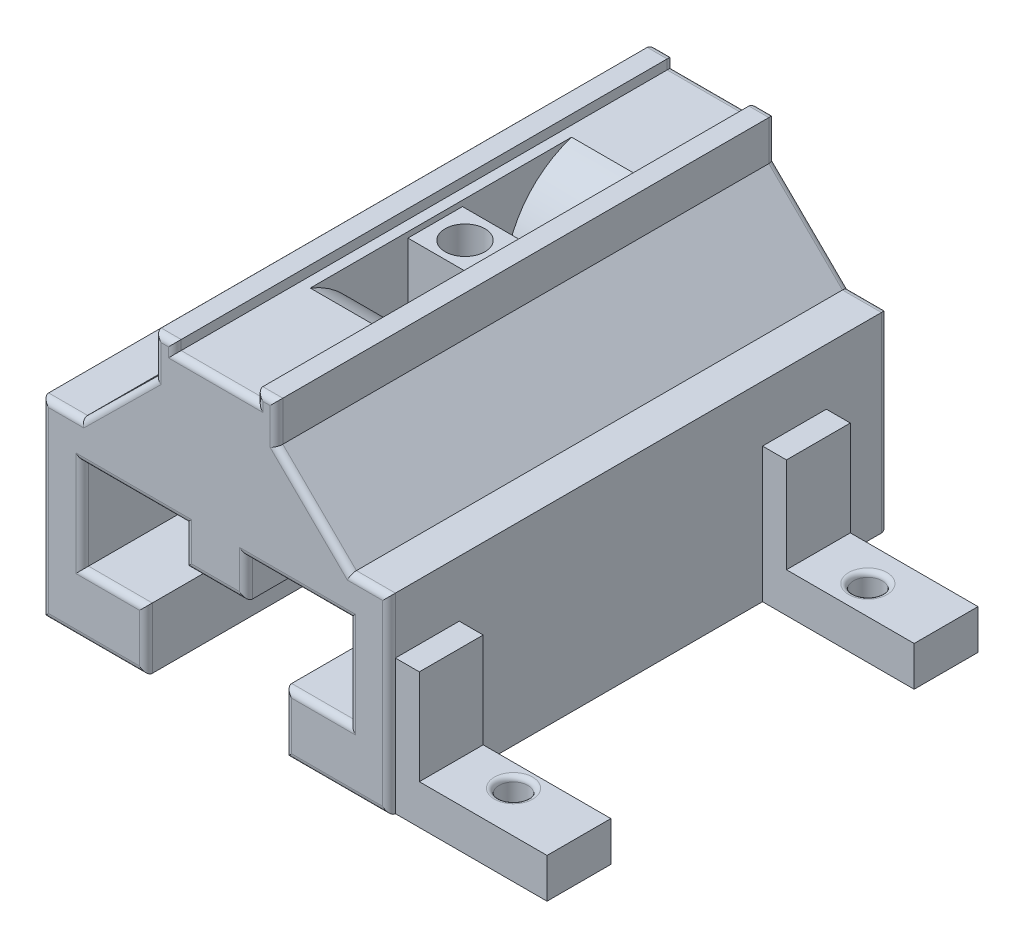
SolidWorks part; units mm, degrees
ref_plane "Front" through (0, 0, 0) normal (0, 0, 1) x (1, 0, 0)
ref_plane "Top" through (0, 0, 0) normal (0, 1, 0) x (1, 0, 0)
ref_plane "Right" through (0, 0, 0) normal (1, 0, 0) x (0, 0, -1)
sketch "Sketch2" plane through (0, 0, 0) normal (0, 0, 1) x (1, 0, 0)
  line L0 (-5.545, 3.0291) -> (-10.62, 3.0291)
  line L1 (-10.62, 3.0291) -> (-10.62, 10.3311)
  line L2 (-10.62, 10.3311) -> (-2.42, 10.3311)
  line L3 (-2.42, 10.3311) -> (-2.42, 7.2831)
  line L4 (-2.42, 7.2831) -> (2.42, 7.2831)
  line L5 (0, -13.7255) -> (0, 13.7255) construction
  line L6 (-5.545, 3.0291) -> (-5.545, -1.8209)
  line L7 (-5.545, -1.8209) -> (-13.795, -1.8209)
  line L8 (-13.795, -1.8209) -> (-13.795, 13.3791)
  line L9 (-13.795, 13.3791) -> (-10.695, 13.3791)
  line L10 (-10.695, 13.3791) -> (-4.8375, 19.1576)
  line L11 (-4.8375, 19.1576) -> (-4.8375, 22.3326)
  line L12 (-4.8375, 22.3326) -> (-3.25, 22.3326)
  line L13 (-3.25, 22.3326) -> (-3.25, 21.5706)
  line L14 (-3.25, 21.5706) -> (3.25, 21.5706)
  line L15 (3.25, 22.3326) -> (3.25, 21.5706)
  line L16 (4.8375, 22.3326) -> (3.25, 22.3326)
  line L17 (4.8375, 19.1576) -> (4.8375, 22.3326)
  line L18 (10.695, 13.3791) -> (4.8375, 19.1576)
  line L19 (13.795, 13.3791) -> (10.695, 13.3791)
  line L20 (13.795, -1.8209) -> (13.795, 13.3791)
  line L21 (5.545, -1.8209) -> (13.795, -1.8209)
  line L22 (5.545, 3.0291) -> (5.545, -1.8209)
  line L23 (2.42, 10.3311) -> (2.42, 7.2831)
  line L24 (10.62, 10.3311) -> (2.42, 10.3311)
  line L25 (10.62, 3.0291) -> (10.62, 10.3311)
  line L26 (5.545, 3.0291) -> (10.62, 3.0291)
  point P23 (0, 21.5706)
  point P32 (0, 7.2831)
  dimension "D1" = 4.85
  dimension "D2" = 8.25
  dimension "D3" = 3.175
  dimension "D4" = 15.2
  dimension "D5" = 3.048
  dimension "D6" = 3.048
  dimension "D7" = 14.2875
  dimension "D8" = 3.175
  dimension "D9" = 0.762
  dimension "D10" = 1.5875
  dimension "D11" = 3.25
  dimension "D12" = 3.1
  dimension "D13" = 8.2
  dimension "D14" = 2.42
extrude "Boss-Extrude1" add sketch "Sketch2" along normal blind 39.6875
sketch "Sketch3" plane through (0, 21.5706, 0) normal (0, 1, 0) x (1, 0, 0)
  line L0 (0, 0) -> (0, -39.6875) construction
  line L1 (-13.795, -19.8438) -> (13.795, -19.8438) construction
  line L2 (-13.795, -39.6875) -> (-13.795, 0) construction
  line L3 (13.795, -39.6875) -> (13.795, 0) construction
  line L4 (3.25, 0) -> (-3.25, 0)
  line L5 (-3.25, 0) -> (-3.25, -39.6875)
  line L6 (-3.25, -39.6875) -> (3.25, -39.6875)
  line L7 (3.25, -39.6875) -> (3.25, 0)
  line L8 (3.25, 0) -> (-3.25, 0)
  line L9 (-3.25, 0) -> (-3.25, -39.6875)
  line L10 (-3.25, -39.6875) -> (3.25, -39.6875)
  line L11 (3.25, -39.6875) -> (3.25, 0)
  circle A0 centre (0, -19.8437) radius 1.5875
  dimension "D2" = 3.175
  dimension "D1" = 0
extrude "Cut-Extrude1" cut sketch "Sketch3" against normal blind 39.6875 contours A0
sketch "Sketch4" plane through (0, 7.2831, 0) normal (0, -1, 0) x (1, 0, 0)
  line L1 (2.0785, 16.2437) -> (4.1569, 19.8437)
  line L2 (4.1569, 19.8437) -> (2.0785, 23.4437)
  line L3 (2.0785, 23.4437) -> (-2.0785, 23.4437)
  line L4 (-2.42, 0) -> (2.42, 0)
  line L5 (2.42, 0) -> (2.42, 39.6875)
  line L6 (2.42, 39.6875) -> (-2.42, 39.6875)
  line L8 (-2.42, 0) -> (2.42, 0)
  line L9 (2.42, 0) -> (2.42, 39.6875)
  line L12 (-2.0785, 23.4437) -> (-4.1569, 19.8437)
  line L13 (-4.1569, 19.8437) -> (-2.0785, 16.2437)
  line L14 (-2.0785, 16.2437) -> (2.0785, 16.2437)
  line L18 (2.42, 39.6875) -> (-2.42, 39.6875)
  line L20 (-2.42, 39.6875) -> (-2.42, 0)
  line L21 (-2.42, 39.6875) -> (-2.42, 0)
  circle A0 centre (0, 19.8437) radius 3.6 construction
  circle M11 centre (0, 19.8437) radius 1.5875
  dimension "D2" = 7.2
  dimension "D1" = 0
extrude "Cut-Extrude3" cut sketch "Sketch4" against normal blind 5 contours M11 | L12 L13 M11 | L13 L14 M11 | L14 L1 M11 | L1 L2 M11 | L2 L3 M11 | L3 L12 M11
sketch "Sketch5" plane through (-2.42, 0, 0) normal (-1, 0, 0) x (0, 0, 1)
  line L6 (30.9355, 21.9296) -> (6.7938, 21.9296)
  line L12 (9.474, 7.2831) -> (17.626, 7.2831)
  line L18 (21.9668, 7.2831) -> (30.1189, 7.2831)
  line L19 (21.9668, 21.1284) -> (17.626, 21.1284)
  line L20 (21.9668, 7.2831) -> (21.9668, 21.1284)
  line L21 (17.626, 21.1284) -> (17.626, 7.2831)
  arc A0 (30.9355, 21.9296) -> (30.1189, 7.2831) centre (32.5149, 14.4955) ccw
  arc A1 (6.7938, 21.9296) -> (9.474, 7.2831) centre (6.631, 14.3314) cw
  dimension "D2" = 4.3408
  dimension "D3" = 7.6
  dimension "D1" = 7.6
  dimension "D4" = 13.8453
  dimension "D5" = 0.8012
  dimension "D6" = 8.1521
extrude "Cut-Extrude5" cut sketch "Sketch5" against normal blind 6.5
sketch "Sketch6" plane through (-3.25, 0, 0) normal (1, 0, 0) x (0, 0, -1)
  line L0 (-26.3863, 10.5206) -> (-13.2066, 10.5206)
  line L1 (-9.474, 7.2831) -> (-30.1189, 7.2831)
fillet "Fillet1" radius 0.508 52 edges at (-8.0825, 3.0291, 0) (-10.62, 6.6801, 0) (6.52, 10.3311, 0) (-2.42, 8.8071, 0) (0, 7.2831, 0) (2.42, 8.8071, 0) (10.62, 6.6801, 0) (8.0825, 3.0291, 0) (5.545, 0.6041, 0) (9.67, -1.8209, 0) (13.795, 5.7791, 0) (12.245, 13.3791, 0) (7.7662, 16.2684, 0) (4.8375, 20.7451, 0) (4.0437, 22.3326, 0) (3.25, 21.9516, 0) (0, 21.5706, 0) (-3.25, 21.9516, 0) (-4.0437, 22.3326, 0) (-4.8375, 20.7451, 0) (-7.7662, 16.2684, 0) (-12.245, 13.3791, 0) (-13.795, 5.7791, 0) (-9.67, -1.8209, 0) (-5.545, 0.6041, 0) (-9.67, -1.8209, 39.6875) (-13.795, 5.7791, 39.6875) (-12.245, 13.3791, 39.6875) (-7.7662, 16.2684, 39.6875) (-4.8375, 20.7451, 39.6875) (-4.0437, 22.3326, 39.6875) (-3.25, 21.9516, 39.6875) (0, 21.5706, 39.6875) (3.25, 21.9516, 39.6875) (4.0437, 22.3326, 39.6875) (4.8375, 20.7451, 39.6875) (7.7662, 16.2684, 39.6875) (12.245, 13.3791, 39.6875) (13.795, 5.7791, 39.6875) (9.67, -1.8209, 39.6875) (5.545, 0.6041, 39.6875) (8.0825, 3.0291, 39.6875) (10.62, 6.6801, 39.6875) (6.52, 10.3311, 39.6875) (2.42, 8.8071, 39.6875) (0, 7.2831, 39.6875) (-2.42, 8.8071, 39.6875) (-10.62, 6.6801, 39.6875) (-8.0825, 3.0291, 39.6875) (-5.545, 0.6041, 39.6875) (-6.52, 10.3311, 0) (-6.52, 10.3311, 39.6875)
sketch "Sketch7" plane through (13.795, 0, 0) normal (1, 0, 0) x (0, 0, -1)
  line L0 (-39.1795, -1.8209) -> (-0.508, -1.8209) construction
  line L1 (-39.1795, -1.8209) -> (-34.0995, -1.8209)
  line L2 (-39.1795, -1.8209) -> (-39.1795, 8.9054)
  line L3 (-39.1795, 8.9054) -> (-34.0995, 8.9054)
  line L4 (-34.0995, -1.8209) -> (-34.0995, 8.9054)
  line L5 (-9.9695, -1.8209) -> (-4.8895, -1.8209)
  line L6 (-9.9695, -1.8209) -> (-9.9695, 8.9054)
  line L7 (-9.9695, 8.9054) -> (-4.8895, 8.9054)
  line L8 (-4.8895, -1.8209) -> (-4.8895, 8.9054)
  dimension "D1" = 5.08
  dimension "D2" = 24.13
extrude "Boss-Extrude2" add sketch "Sketch7" along normal blind 1.905
sketch "Sketch8" plane through (15.7, 0, 0) normal (1, 0, 0) x (0, 0, -1)
  line L0 (-39.1795, 1.336) -> (-34.0995, 1.336)
  line L1 (-9.9695, 1.336) -> (-4.8895, 1.336)
  line L4 (-39.1795, 8.9054) -> (-39.1795, -1.8209)
  line L5 (-39.1795, -1.8209) -> (-34.0995, -1.8209)
  line L6 (-34.0995, -1.8209) -> (-34.0995, 8.9054)
  line L7 (-34.0995, 8.9054) -> (-39.1795, 8.9054)
  line L8 (-39.1795, 8.9054) -> (-39.1795, -1.8209)
  line L9 (-39.1795, -1.8209) -> (-34.0995, -1.8209)
  line L10 (-34.0995, -1.8209) -> (-34.0995, 8.9054)
  line L11 (-34.0995, 8.9054) -> (-39.1795, 8.9054)
  line L12 (-9.9695, 8.9054) -> (-9.9695, -1.8209)
  line L13 (-9.9695, -1.8209) -> (-4.8895, -1.8209)
  line L14 (-4.8895, -1.8209) -> (-4.8895, 8.9054)
  line L15 (-4.8895, 8.9054) -> (-9.9695, 8.9054)
  line L16 (-9.9695, 8.9054) -> (-9.9695, -1.8209)
  line L17 (-9.9695, -1.8209) -> (-4.8895, -1.8209)
  line L18 (-4.8895, -1.8209) -> (-4.8895, 8.9054)
  line L19 (-4.8895, 8.9054) -> (-9.9695, 8.9054)
  line M9 (-39.1795, 8.9054) -> (-39.1795, -1.8209)
  line M10 (-39.1795, -1.8209) -> (-34.0995, -1.8209)
  line M11 (-34.0995, -1.8209) -> (-34.0995, 8.9054)
  dimension "D1" = 0
  dimension "D2" = 0
extrude "Boss-Extrude3" add sketch "Sketch8" along normal blind 10.16 contours L0 M9 M10 M11 | L17 L18 L1 L16
sketch "Sketch9" plane through (0, -1.8209, 0) normal (0, -1, 0) x (1, 0, 0)
  line L11 (5.545, 39.1795) -> (5.545, 0.508)
  line L12 (5.545, 0.508) -> (13.795, 0.508)
  line L13 (13.795, 0.508) -> (13.795, 4.8895)
  line L14 (13.795, 4.8895) -> (25.86, 4.8895)
  line L15 (25.86, 4.8895) -> (25.86, 9.9695)
  line L16 (25.86, 9.9695) -> (13.795, 9.9695)
  line L17 (13.795, 9.9695) -> (13.795, 34.0995)
  line L18 (13.795, 34.0995) -> (25.86, 34.0995)
  line L19 (25.86, 34.0995) -> (25.86, 39.1795)
  line L20 (25.86, 39.1795) -> (13.795, 39.1795)
  line L21 (13.795, 39.1795) -> (5.545, 39.1795)
  line L22 (5.545, 39.1795) -> (5.545, 0.508)
  line L23 (5.545, 0.508) -> (13.795, 0.508)
  line L24 (13.795, 0.508) -> (13.795, 4.8895)
  line L25 (13.795, 4.8895) -> (25.86, 4.8895)
  line L26 (25.86, 4.8895) -> (25.86, 9.9695)
  line L27 (25.86, 9.9695) -> (13.795, 9.9695)
  line L28 (13.795, 9.9695) -> (13.795, 34.0995)
  line L29 (13.795, 34.0995) -> (25.86, 34.0995)
  line L30 (25.86, 34.0995) -> (25.86, 39.1795)
  line L31 (25.86, 39.1795) -> (13.795, 39.1795)
  line L32 (13.795, 39.1795) -> (5.545, 39.1795)
  circle A0 centre (19.891, 7.6835) radius 1.143
  circle A1 centre (19.891, 35.8775) radius 1.143
  dimension "D2" = 2.286
  dimension "D4" = 2.286
  dimension "D6" = 6.096
  dimension "D7" = 6.096
  dimension "D3" = 2.286
  dimension "D5" = 1.778
  dimension "D1" = 0
extrude "Cut-Extrude7" cut sketch "Sketch9" against normal up to next contours A1 | A0
fillet "Fillet2" radius 0.381 4 edges at (21.034, -1.8209, 7.6835) (21.034, -1.8209, 35.8775) (18.748, 1.336, 7.6835) (18.748, 1.336, 35.8775)
